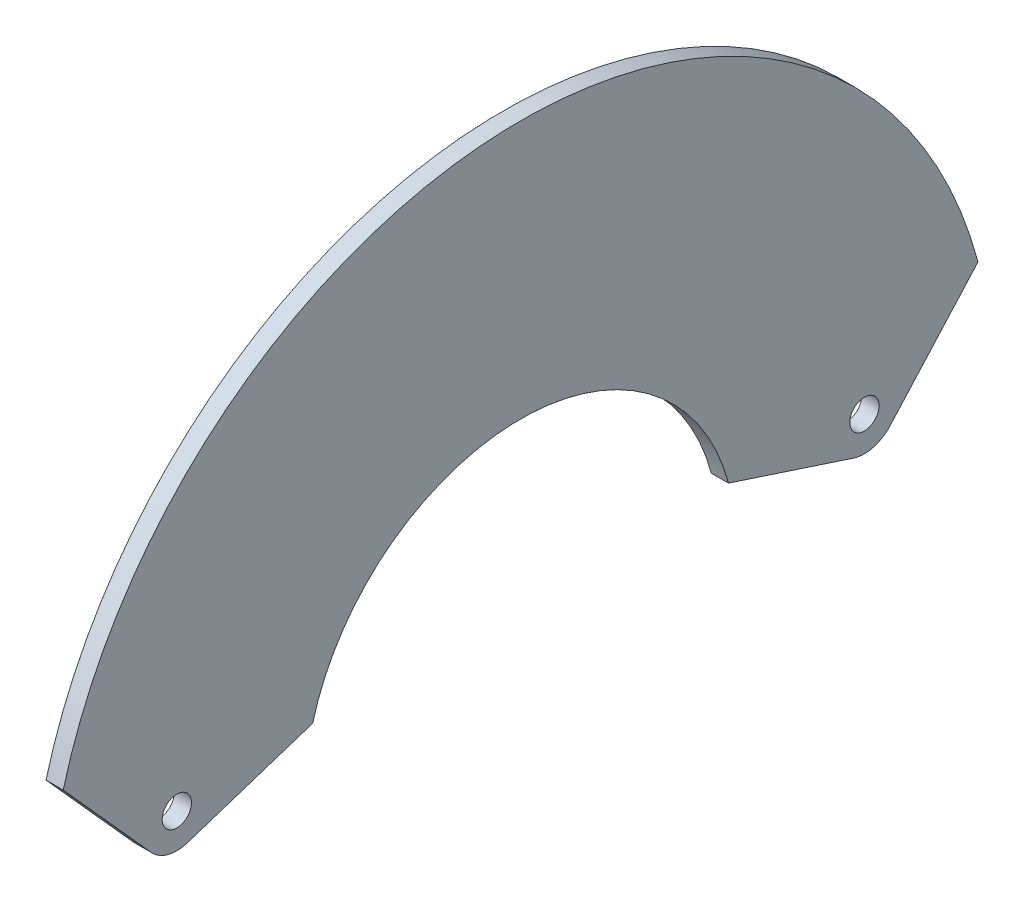
SolidWorks part; units mm, degrees
ref_plane "Front" through (0, 0, 0) normal (0, 0, 1) x (1, 0, 0)
ref_plane "Top" through (0, 0, 0) normal (0, 1, 0) x (1, 0, 0)
ref_plane "Right" through (0, 0, 0) normal (1, 0, 0) x (0, 0, -1)
sketch "Sketch1" plane through (0, 0, 0) normal (1, 0, 0) x (0, 0, -1)
  line L0 (0, 60) -> (-53.1259, 74.235) construction
  line L1 (53.1259, 74.235) -> (0, 60) construction
  line L2 (0, 60) -> (-53.1259, 74.235)
  line L3 (53.1259, 74.235) -> (0, 60)
  line L4 (42.9079, 62.8512) -> (53.1259, 74.235)
  line L5 (38.6892, 61.7208) -> (24.1481, 66.4705)
  line L6 (0, 50) -> (0, -50) construction
  line L7 (-38.6892, 61.7208) -> (-24.1481, 66.4705)
  line L8 (-42.9079, 62.8512) -> (-53.1259, 74.235)
  arc A0 (24.1481, 66.4705) -> (-24.1481, 66.4705) centre (0, 60) ccw construction
  arc A1 (53.1259, 74.235) -> (-53.1259, 74.235) centre (0, 60) ccw construction
  arc A2 (24.1481, 66.4705) -> (-24.1481, 66.4705) centre (0, 60) ccw
  arc A3 (53.1259, 74.235) -> (-53.1259, 74.235) centre (0, 60) ccw
  circle A4 centre (-39.9311, 65.5231) radius 1.5 construction
  circle A5 centre (39.9311, 65.5231) radius 1.5 construction
  circle A6 centre (-39.9311, 65.5231) radius 1.5
  circle A7 centre (39.9311, 65.5231) radius 1.5
  arc A8 (42.9079, 62.8512) -> (38.6892, 61.7208) centre (39.9311, 65.5231) cw
  arc A9 (-42.9079, 62.8512) -> (-38.6892, 61.7208) centre (-39.9311, 65.5231) ccw
  circle A10 centre (39.9311, 65.5231) radius 1.7
  circle A11 centre (-39.9311, 65.5231) radius 1.7
  dimension "D1" = 4
  dimension "D2" = 3.4
  dimension "D3" = 3.4
extrude "Boss-Extrude1" add sketch "Sketch1" against normal blind 2 contours L3 A3 L2 A2 | A8 L4 L3 L5 A7 | L8 A9 L7 L2 A6
